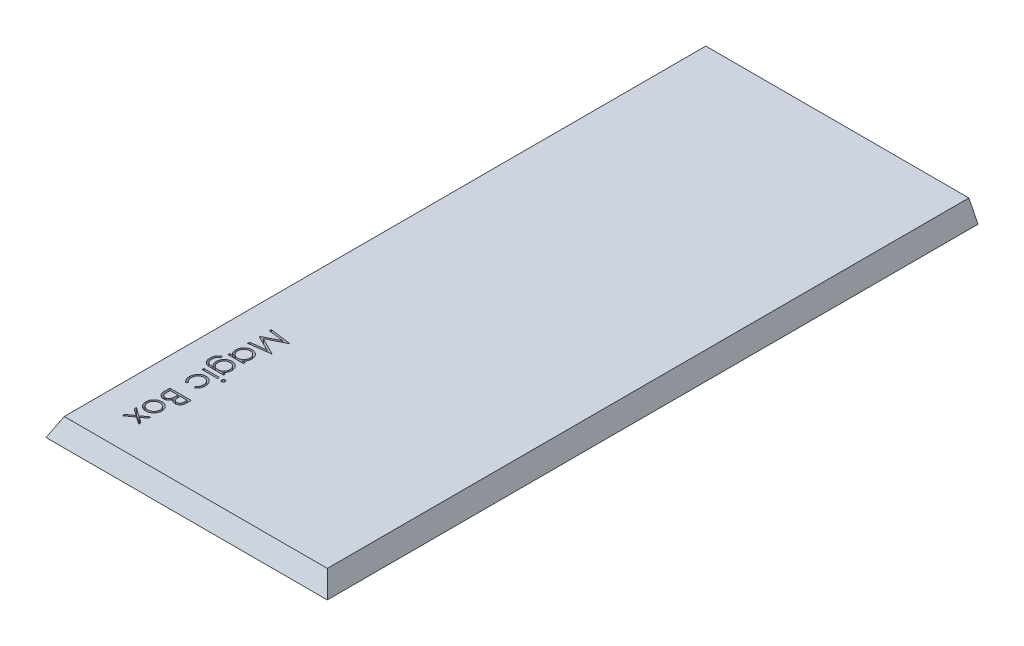
SolidWorks part; units mm, degrees
ref_plane "Front Plane" through (0, 0, 0) normal (0, 0, 1) x (1, 0, 0)
ref_plane "Top Plane" through (0, 0, 0) normal (0, 1, 0) x (1, 0, 0)
ref_plane "Right Plane" through (0, 0, 0) normal (1, 0, 0) x (0, 0, -1)
sketch "Sketch1" plane through (0, 0, 0) normal (0, 1, 0) x (1, 0, 0)
  line L1 (0, 0) -> (47, 0)
  line L2 (0, 0) -> (0, -107.5)
  line L3 (0, -107.5) -> (47, -107.5)
  line L4 (47, 0) -> (47, -107.5)
  dimension "D1" = 47
  dimension "D2" = 107.5
extrude "Boss-Extrude1" add sketch "Sketch1" along normal blind 3
sketch "Sketch2" plane through (0, 3, 0) normal (0, 1, 0) x (1, 0, 0)
  line L0 (6.5, -107.5) -> (6.5, -68.0831) construction
  line L1 (0, -107.5) -> (47, -107.5) construction
  text T0 "Magic Box     \r\n\r\n"
  dimension "D1" = 6.5
extrude "Cut-Extrude2" cut sketch "Sketch2" against normal blind 1
sketch "Sketch3" plane through (0, 0, 0) normal (0, 0, -1) x (-1, 0, 0)
  line L0 (0.3, 3.3) -> (-1.9854, 3.3)
  line L2 (-47, 3) -> (-47, 0)
  line L17 (-47, 3) -> (-45.5, 3)
  line L18 (-47, 3) -> (0, 3) construction
  line L19 (-1.9854, 3.3) -> (0.3, -1.2708)
  line L20 (-47, 0) -> (-45.5, 3)
  line L21 (0, 3) -> (-1.5, 3)
  line L22 (0, 3) -> (0, 0)
  line L25 (-1.5, 3) -> (0, 0)
  line L26 (-47.3, 3.3) -> (-45.0146, 3.3)
  line L27 (-47.3, -1.2708) -> (-45.0146, 3.3)
  line L28 (-47.3, 3.3) -> (-47.3, -1.2708)
  line L29 (0.3, 3.3) -> (0.3, -1.2708)
  line M15 (-47, 0) -> (0, 0)
  line M16 (0, 0) -> (0, 3)
  line M17 (0, 3) -> (-47, 3)
  line M18 (-47, 3) -> (-47, 0)
  dimension "D1" = 1.5
  dimension "D2" = 0.3
  dimension "D3" = 0.3
sketch "Sketch4" plane through (0, 0, 0) normal (-1, 0, 0) x (0, 0, 1)
  line L7 (107.8, 3.3) -> (105.5146, 3.3)
  line L10 (107.5, 3) -> (106, 3)
  line L12 (107.5, 3) -> (107.5, 0)
  line L15 (106, 3) -> (107.5, 0)
  line L16 (105.5146, 3.3) -> (107.8, -1.2708)
  line L17 (107.8, 3.3) -> (107.8, -1.2708)
  dimension "D1" = 1.5
  dimension "D2" = 0.3
extrude "Cut-Extrude7" cut sketch "Sketch4" against normal blind 109 contours L7 L16 L17
extrude "Cut-Extrude10" cut sketch "Sketch3" against normal blind 109 contours L26 L28 L27 M15 M18 M17 | L27 L20 M15 M17 | L20 M18 M17 | L25 L19 M17 M15 | L25 M17 M16
